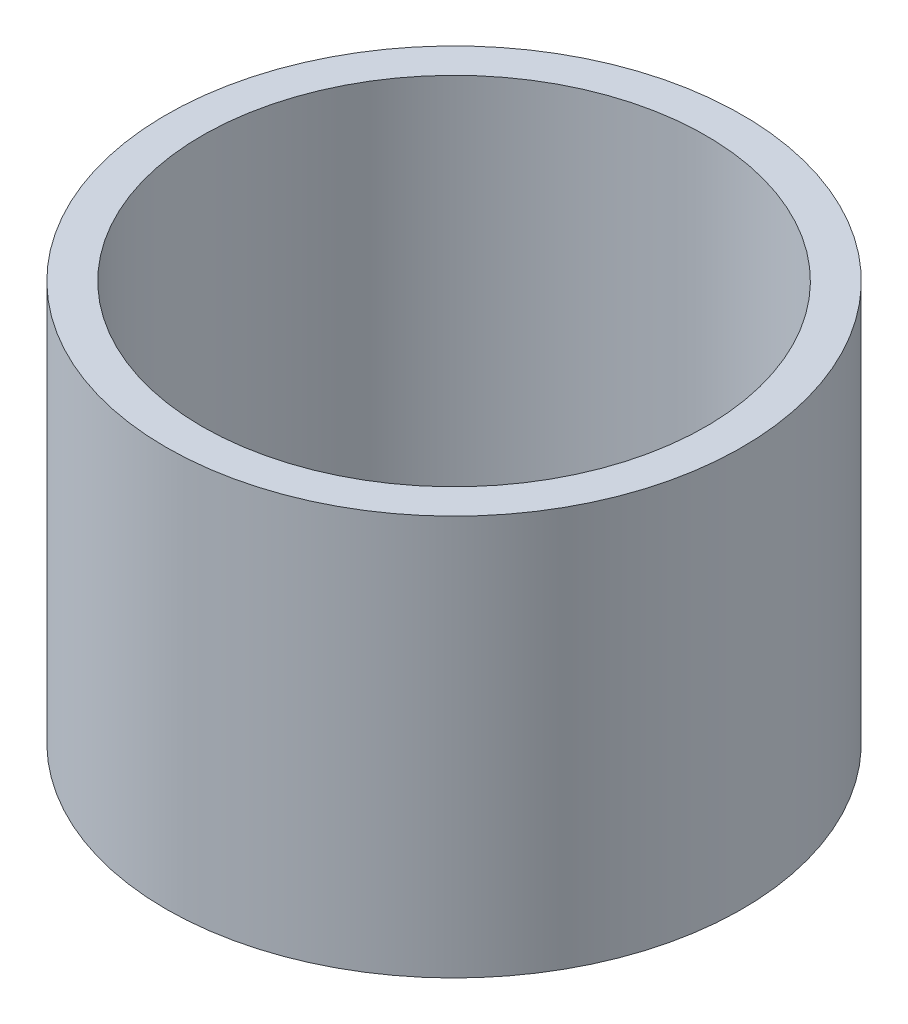
SolidWorks part; units mm, degrees
ref_plane "Front Plane" through (0, 0, 0) normal (0, 0, 1) x (1, 0, 0)
ref_plane "Top Plane" through (0, 0, 0) normal (0, 1, 0) x (1, 0, 0)
ref_plane "Right Plane" through (0, 0, 0) normal (1, 0, 0) x (0, 0, -1)
sketch "Sketch1" plane through (0, 0, 0) normal (0, 1, 0) x (1, 0, 0)
  circle A0 centre (0, 0) radius 3.6
extrude "Boss-Extrude1" add sketch "Sketch1" along normal blind 5
sketch "Sketch2" plane through (0, 5, 0) normal (0, 1, 0) x (1, 0, 0)
  circle A0 centre (0, 0) radius 3.15
extrude "Cut-Extrude1" cut sketch "Sketch2" against normal blind 4.5
